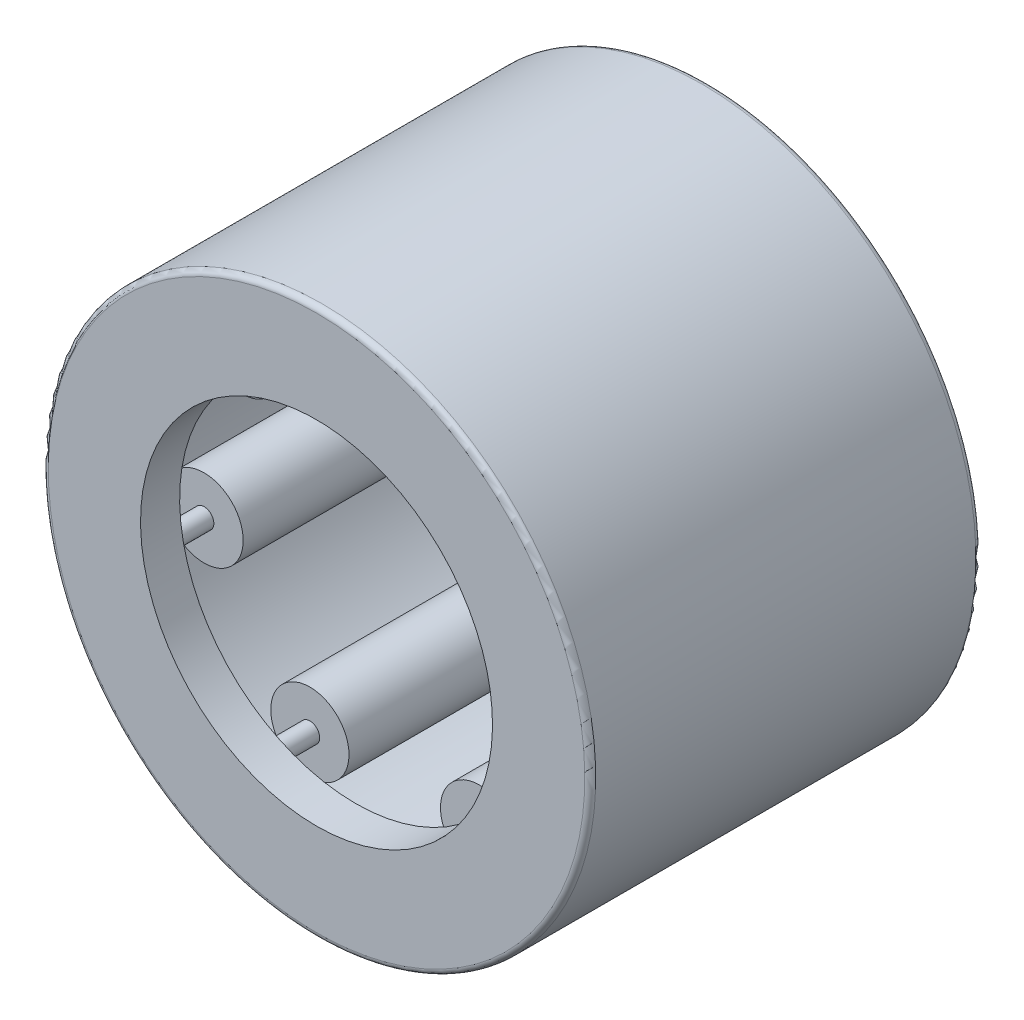
SolidWorks part; units mm, degrees
material "1023 Carbon Steel Sheet (SS)"
ref_plane "Front Plane" through (0, 0, 0) normal (0, 0, 1) x (1, 0, 0)
ref_plane "Top Plane" through (0, 0, 0) normal (0, 1, 0) x (1, 0, 0)
ref_plane "Right Plane" through (0, 0, 0) normal (1, 0, 0) x (0, 0, -1)
sketch "Sketch1" plane through (0, 0, 0) normal (1, 0, 0) x (0, 0, -1)
  line L0 (-3.9688, 0) -> (3.9688, 0) construction
  line L1 (0, 0) -> (0, 5.5562) construction
  line L2 (-3.9688, 0) -> (-3.9688, 5.5562) construction
  line L3 (-3.9688, 5.5562) -> (3.9688, 5.5562)
  line L4 (3.9688, 5.5562) -> (3.9688, 0) construction
  line L5 (3.9688, 0) -> (3.175, 0) construction
  line L6 (3.175, 0) -> (3.175, 4.7625) construction
  line L7 (3.175, 4.7625) -> (-3.175, 4.7625)
  line L8 (-3.175, 4.7625) -> (-3.175, 0) construction
  line L9 (-3.175, 0) -> (-3.9688, 0) construction
  line L10 (-3.9688, 5.5562) -> (-3.9688, 3.5719)
  line L11 (-3.9688, 3.5719) -> (-3.175, 3.5719)
  line L12 (-3.175, 3.5719) -> (-3.175, 4.7625)
  line L13 (3.175, 5.5562) -> (3.175, 4.7625) construction
  line L14 (3.175, 4.7625) -> (3.175, 3.5719)
  line L15 (3.175, 3.5719) -> (3.9688, 3.5719)
  line L16 (3.9688, 3.5719) -> (3.9688, 5.5562)
  line L17 (3.175, 4.7625) -> (3.175, 3.9687) construction
  line L18 (3.175, 3.9687) -> (3.175, 3.175) construction
  line L19 (3.175, -4.7625) -> (3.175, -3.9687) construction
  line L20 (3.175, -5.5562) -> (3.175, -4.7625) construction
  line L21 (3.9688, -3.5719) -> (3.9688, -5.5562) construction
  line L22 (3.175, -3.5719) -> (3.9688, -3.5719) construction
  line L23 (3.175, -4.7625) -> (3.175, -3.5719) construction
  line L24 (-3.175, -3.5719) -> (-3.175, -4.7625) construction
  line L25 (-3.9688, -3.5719) -> (-3.175, -3.5719) construction
  line L26 (-3.9688, -5.5562) -> (-3.9688, -3.5719) construction
  line L27 (3.175, -4.7625) -> (-3.175, -4.7625) construction
  line L28 (-3.9688, -5.5562) -> (3.9688, -5.5562) construction
  point P5 (0, 3.175)
  dimension "Width" = 7.9375
  dimension "OD" = 11.1125
  dimension "Shaft Dia" = 6.35
revolve "Revolve1" add sketch "Sketch1" angle 360 about L0
sketch "Sketch2" plane through (0, 0, 0) normal (1, 0, 0) x (0, 0, -1)
  line L0 (3.175, 4.7625) -> (-3.175, 4.7625) construction
  line L1 (-2.3813, 3.9687) -> (2.3813, 3.9687) construction
  line L2 (-2.3813, 3.9687) -> (-2.3813, 4.7625) construction
  line L3 (-2.3813, 4.7625) -> (2.3813, 4.7625)
  line L4 (2.3813, 3.9687) -> (2.3813, 4.7625) construction
  line L5 (3.175, 3.5719) -> (3.9688, 3.5719) construction
  line L6 (-3.175, 3.9687) -> (-2.3813, 3.9687) construction
  line L7 (2.3813, 3.9687) -> (3.175, 3.9687) construction
  line L8 (-3.9688, 3.5719) -> (-3.175, 3.5719) construction
  line L9 (-2.3813, 4.1672) -> (-2.3813, 3.7703) construction
  line L10 (-3.175, 3.9687) -> (-3.175, 3.5719) construction
  line L11 (-2.3813, 4.7625) -> (-2.3813, 4.1672)
  line L12 (2.3813, 4.7625) -> (2.3813, 4.1672)
  line L13 (2.3813, 4.1672) -> (-2.3813, 4.1672)
  line L14 (0, 4.7625) -> (0, 3.175) construction
  line L15 (-3.175, 3.5719) -> (-3.175, 4.7625) construction
  line L16 (-2.3813, 3.7703) -> (-3.175, 3.7703) construction
  line L17 (0, 0) -> (3.9688, 0) construction
  line L18 (-2.3813, -3.7703) -> (-3.175, -3.7703) construction
  line L19 (0, -4.7625) -> (0, -3.175) construction
  line L20 (-3.175, -3.9687) -> (-3.175, -3.5719) construction
  line L21 (-2.3813, -4.1672) -> (-2.3813, -3.7703) construction
  line L22 (2.3813, -3.9687) -> (3.175, -3.9687) construction
  line L23 (-3.175, -3.9687) -> (-2.3812, -3.9687) construction
  line L24 (2.3813, -3.9687) -> (2.3813, -4.7625) construction
  line L25 (-2.3812, -3.9687) -> (-2.3813, -4.7625) construction
  line L26 (-2.3812, -3.9687) -> (2.3813, -3.9687) construction
  line L27 (2.3813, -4.1672) -> (-2.3813, -4.1672) construction
  line L28 (2.3813, -4.7625) -> (2.3813, -4.1672) construction
  line L29 (-2.3813, -4.7625) -> (-2.3813, -4.1672) construction
  line L30 (-2.3813, -4.7625) -> (2.3813, -4.7625) construction
  line L31 (3.9688, -5.5563) -> (3.9688, 5.5562) construction
  point P16 (0, 3.9687)
revolve "Revolve2" add sketch "Sketch2" angle 360 about L1
sketch "Sketch3" plane through (0, 0, 0) normal (1, 0, 0) x (0, 0, -1)
  line L0 (3.175, 4.7625) -> (3.175, 3.5719) construction
  line L1 (-3.175, 3.9687) -> (3.175, 3.9687)
  line L2 (-3.175, 3.9687) -> (-3.175, 4.1672)
  line L3 (-3.175, 4.1672) -> (3.175, 4.1672)
  line L4 (3.175, 3.9687) -> (3.175, 4.1672)
  line L5 (0, 0) -> (3.9688, 0) construction
  line L6 (3.9688, -5.5563) -> (3.9688, 5.5562) construction
  line L7 (3.175, -3.9687) -> (3.175, -4.1672) construction
  line L8 (-3.175, -4.1672) -> (3.175, -4.1672) construction
  line L9 (-3.175, -3.9687) -> (-3.175, -4.1672) construction
  line L10 (-3.175, -3.9687) -> (3.175, -3.9687) construction
revolve "Revolve3" add sketch "Sketch3" angle 360 about L1
ref_axis "Axis1" through (0, 0, -3.9688) along (0, 0, 1)
pattern_circular "CirPattern1" count 7 every 51.429 about axis through (0, 0, -3.9688) along (0, 0, 1) of bodies 166 167
fillet "Fillet1" radius 0.1111 2 edges at (0, -5.5563, -3.9688) (0, -5.5562, 3.9688)
sketch "Sketch4" plane through (0, 0, 0) normal (1, 0, 0) x (0, 0, -1)
  line L1 (3.8576, 3.175) -> (2.3813, 3.175)
  line L2 (3.8576, 3.175) -> (3.8576, 3.5719)
  line L3 (3.8576, 3.5719) -> (2.3813, 3.5719)
  line L4 (2.3813, 3.175) -> (2.3813, 3.5719)
  line L5 (-3.9688, 3.5719) -> (-3.175, 3.5719) construction
  line L6 (3.8576, -5.5563) -> (3.8576, 5.5562) construction
  line L7 (2.3813, 4.7625) -> (2.3813, 4.1672) construction
revolve "Revolve4" [suppressed] add sketch "Sketch4" angle 360 about L0
sketch "Sketch5" plane through (0, 0, 0) normal (1, 0, 0) x (0, 0, -1)
  line L0 (-3.8576, 5.5563) -> (-3.8576, -5.5563) construction
  line L1 (-2.3813, 3.175) -> (-3.8576, 3.175)
  line L2 (-2.3813, 3.175) -> (-2.3813, 3.5719)
  line L3 (-2.3813, 3.5719) -> (-3.8576, 3.5719)
  line L4 (-3.8576, 3.175) -> (-3.8576, 3.5719)
  line L6 (-2.3813, 4.7625) -> (-2.3813, 4.1672) construction
  line L7 (-3.9688, 3.5719) -> (-3.175, 3.5719) construction
revolve "Revolve5" [suppressed] add sketch "Sketch5" angle 360 about L0
equation "\"Angle@CirPattern1\" = 360/\"Rollers@CirPattern1\""
equation "\"Rollers@CirPattern1\" = \"OD@Sketch1\"*16"
equation "\"D1@Fillet1\" = \"OD@Sketch1\"*.01"
